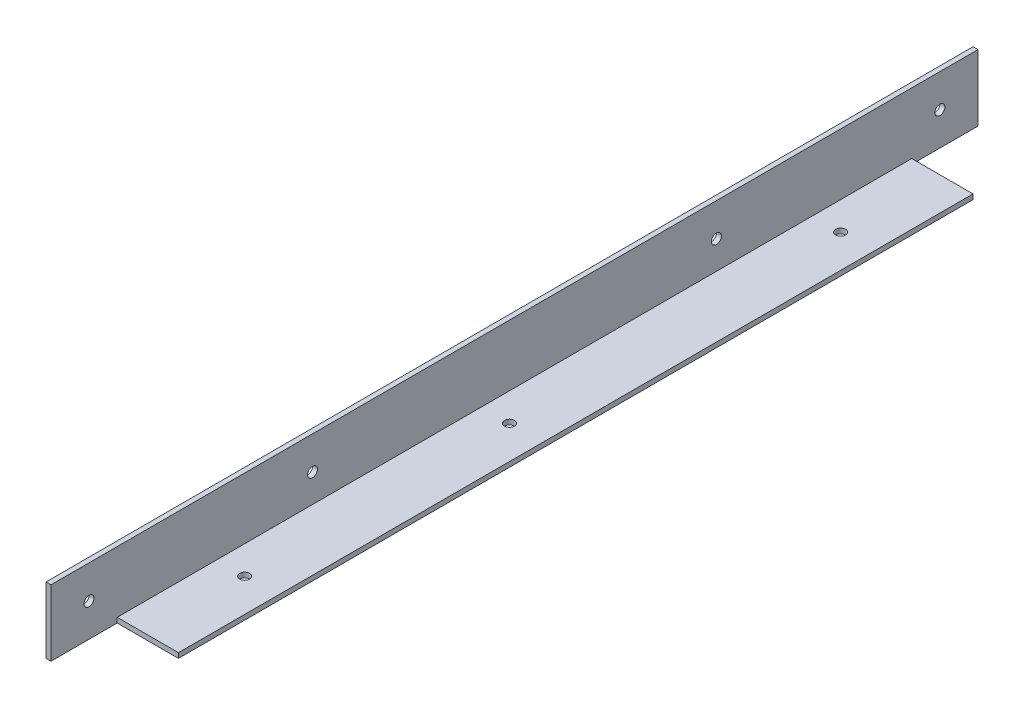
SolidWorks part; units mm, degrees
ref_plane "Plan de face" through (0, 0, 0) normal (0, 0, 1) x (1, 0, 0)
ref_plane "Plan de dessus" through (0, 0, 0) normal (0, 1, 0) x (1, 0, 0)
ref_plane "Plan de droite" through (0, 0, 0) normal (1, 0, 0) x (0, 0, -1)
sketch "Esquisse1" plane through (0, 0, 0) normal (0, 0, 1) x (1, 0, 0)
  line L0 (0, 0) -> (20, 0)
  line L1 (20, 0) -> (20, 1.5)
  line L2 (20, 1.5) -> (1.5, 1.5)
  line L3 (1.5, 1.5) -> (1.5, 20)
  line L4 (1.5, 20) -> (0, 20)
  line L5 (0, 20) -> (0, 0)
  dimension "D1" = 1.5
  dimension "D2" = 1.5
  dimension "D3" = 20
  dimension "D4" = 20
extrude "Extrusion1" add sketch "Esquisse1" along normal blind 240
sketch "Esquisse2" plane through (0, 1.5, 0) normal (0, 1, 0) x (1, 0, 0)
  line L0 (20, -240) -> (20, 0) construction
  line L1 (20, 0) -> (1.5, 0) construction
  line L2 (20, -240) -> (1.5, -240) construction
  circle A0 centre (10, -30) radius 1.5
  circle A1 centre (10, -210) radius 1.5
  circle A2 centre (10, -130) radius 1.5
  point P8 (10.75, -240)
  dimension "D7" = 130
  dimension "D1" = 10
  dimension "D2" = 30
  dimension "D5" = 30
  dimension "D6" = 10
extrude "Extrusion2" cut sketch "Esquisse2" against normal through all
sketch "Esquisse3" plane through (0, 0, 240) normal (0, 0, 1) x (1, 0, 0)
  line L0 (0, 20) -> (1.5, 20)
  line L1 (1.5, 20) -> (1.5, 0)
  line L2 (0, 0) -> (20, 0) construction
  line L3 (1.5, 0) -> (0, 0)
  line L4 (0, 0) -> (0, 20)
extrude "Extrusion3" add sketch "Esquisse3" along normal blind 20
sketch "Esquisse5" plane through (0, 0, 0) normal (0, 0, -1) x (-1, 0, 0)
  line L0 (-1.5, 20) -> (0, 20)
  line L1 (0, 20) -> (0, 0)
  line L2 (0, 0) -> (-1.5, 0)
  line L3 (-1.5, 0) -> (-1.5, 20)
extrude "Extrusion4" add sketch "Esquisse5" along normal blind 20
sketch "Esquisse6" plane through (1.5, 0, 0) normal (1, 0, 0) x (0, 0, -1)
  line L0 (-260, 0) -> (-260, 20) construction
  line L1 (-260, 0) -> (-240, 0) construction
  line L2 (20, 20) -> (20, 0) construction
  circle A0 centre (-248.5, 10) radius 1.5
  circle A1 centre (8.5, 10) radius 1.5
  circle A2 centre (-181, 10) radius 1.5
  circle A3 centre (-59, 10) radius 1.5
  point P2 (-260, 10)
  dimension "D3" = 11.5
  dimension "D4" = 79
  dimension "D1" = 11.5
  dimension "D2" = 10
  dimension "D5" = 79
extrude "Extrusion5" cut sketch "Esquisse6" against normal through all
